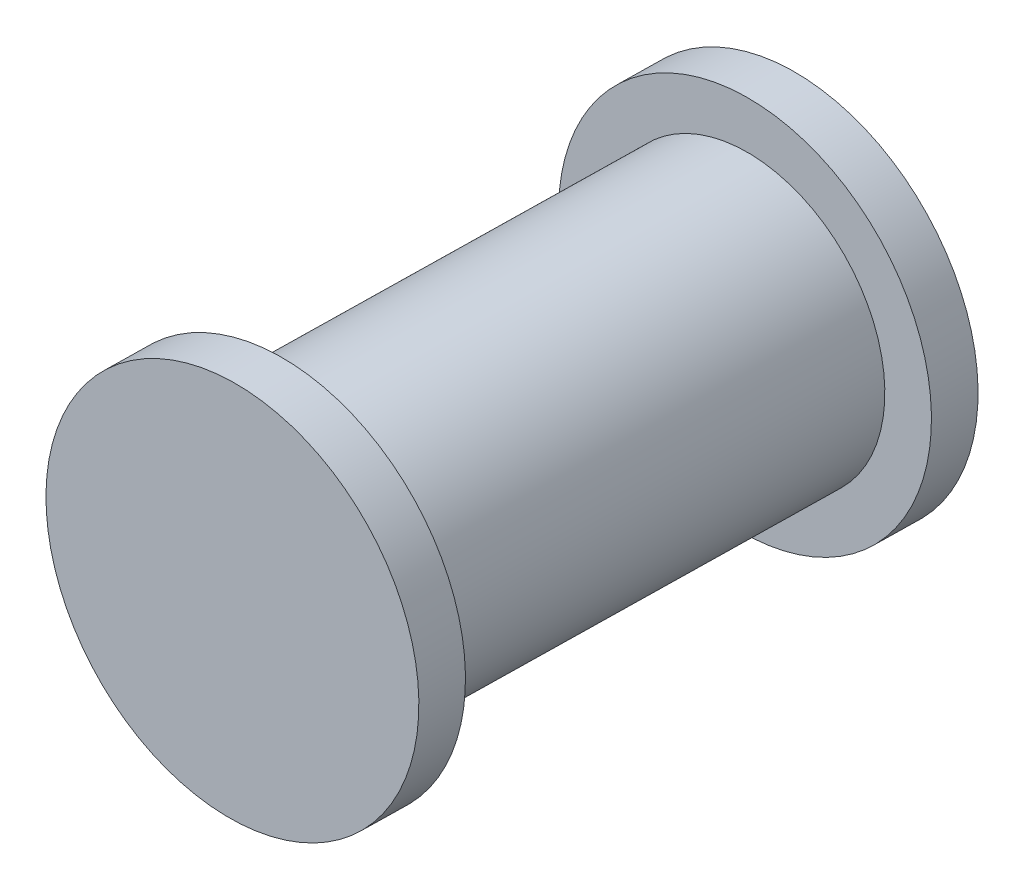
SolidWorks part; units mm, degrees
material "Alumina"
ref_plane "Front Plane" through (0, 0, 0) normal (0, 0, 1) x (1, 0, 0)
ref_plane "Top Plane" through (0, 0, 0) normal (0, 1, 0) x (1, 0, 0)
ref_plane "Right Plane" through (0, 0, 0) normal (1, 0, 0) x (0, 0, -1)
sketch "Sketch1" plane through (0, 0, 0) normal (0, 0, 1) x (1, 0, 0)
  line L0 (0, 0) -> (0, 12)
  line L3 (-3, 1) -> (-4, 1)
  line L4 (-4, 1) -> (-4, 0)
  line L5 (-4, 0) -> (0, 0)
  line L6 (0, 12) -> (-4, 12)
  line L7 (-4, 12) -> (-4, 11)
  line L8 (-4, 11) -> (-3, 11)
  line L9 (-3, 11) -> (-3, 1)
  dimension "D1" = 12
  dimension "D2" = 1
  dimension "D3" = 4
  dimension "D4" = 3
revolve "Revolve1" add sketch "Sketch1" angle 360 about L0
move or copy body "Body-Move/Copy1" bodies to move or copy 101 copy no rotation origin (-2.3466, 4.6121, -2.3466) rotation axis (0.574, 0.5841, 0.574) rotation angle 119.424
